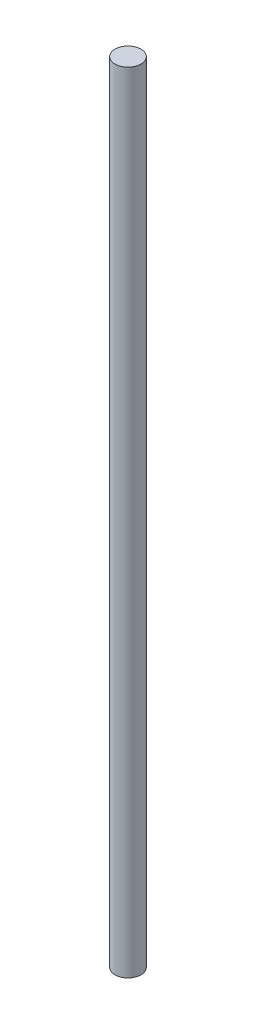
SolidWorks part; units mm, degrees
ref_plane "Front Plane" through (0, 0, 0) normal (0, 0, 1) x (1, 0, 0)
ref_plane "Top Plane" through (0, 0, 0) normal (0, 1, 0) x (1, 0, 0)
ref_plane "Right Plane" through (0, 0, 0) normal (1, 0, 0) x (0, 0, -1)
sketch "Sketch1" plane through (0, 0, 0) normal (0, 1, 0) x (1, 0, 0)
  circle A0 centre (0, 0) radius 0.625
  dimension "D1" = 1.25
extrude "Boss-Extrude1" add sketch "Sketch1" along normal blind 38
